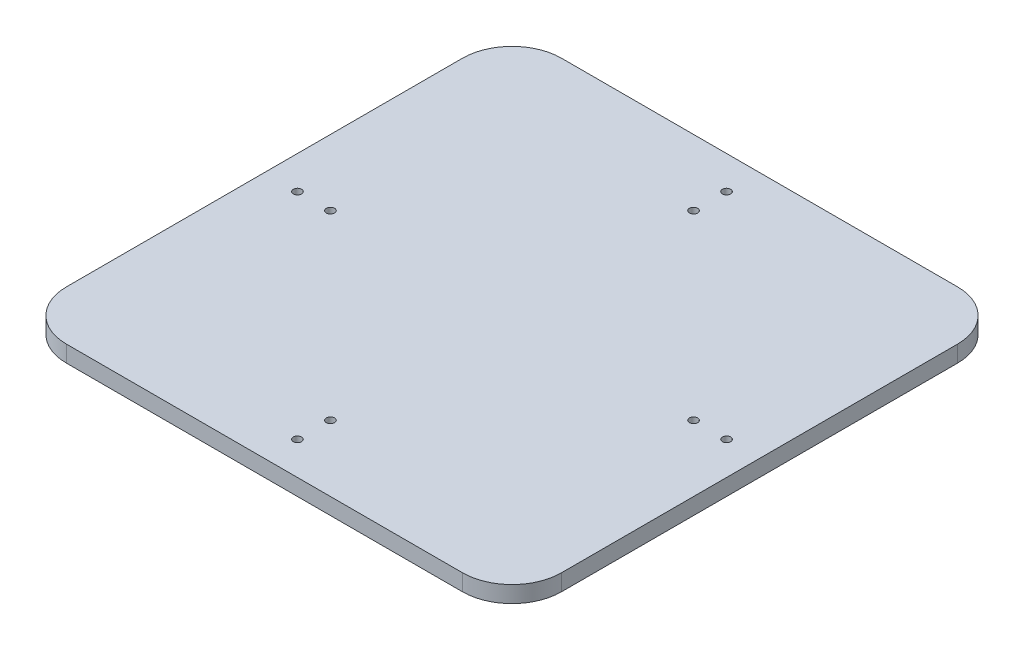
SolidWorks part; units mm, degrees
ref_plane "Front Plane" through (0, 0, 0) normal (0, 0, 1) x (1, 0, 0)
ref_plane "Top Plane" through (0, 0, 0) normal (0, 1, 0) x (1, 0, 0)
ref_plane "Right Plane" through (0, 0, 0) normal (1, 0, 0) x (0, 0, -1)
sketch "Sketch1" plane through (0, 0, 0) normal (0, 1, 0) x (1, 0, 0)
  line L0 (0, 75) -> (0, -75) construction
  line L1 (-75, -75) -> (75, -75)
  line L2 (-75, -75) -> (-75, 75)
  line L3 (-75, 75) -> (75, 75)
  line L4 (75, -75) -> (75, 75)
  line L5 (-75, -75) -> (75, 75) construction
  line L6 (-75, 75) -> (75, -75) construction
  line L7 (-75, 0) -> (75, 0) construction
  line L8 (-75, -60) -> (-60, -60) construction
  line L9 (-60, -60) -> (-60, -75) construction
  arc A2 (-75, -60) -> (-60, -75) centre (-60, -60) ccw
  arc A3 (75, -60) -> (60, -75) centre (60, -60) cw
  arc A4 (-75, 60) -> (-60, 75) centre (-60, 60) cw
  arc A5 (75, 60) -> (60, 75) centre (60, 60) ccw
  point P0 (0, 0)
  dimension "D6" = 15
  dimension "D4" = 15
  dimension "D1" = 150
  dimension "D2" = 150
extrude "Boss-Extrude3" add sketch "Sketch1" along normal blind 4 contours L4 A5 L3 A4 L2 A2 L1 A3
sketch "Sketch2" plane through (0, 4, 0) normal (0, 1, 0) x (1, 0, 0)
  line L0 (-60, 75) -> (60, 75)
  line L1 (75, 60) -> (75, -60)
  line L2 (60, -75) -> (-60, -75)
  line L3 (-75, -60) -> (-75, 60)
  line L4 (75, 0) -> (-75, 0) construction
  line L5 (0, 75) -> (0, -75) construction
  line L6 (0, 0) -> (-150, 0) construction
  line L7 (75, 0) -> (150, 0) construction
  line L8 (0, 75) -> (0, 150) construction
  line L9 (0, -75) -> (0, -150) construction
  line L10 (-150, 120) -> (-150, -120)
  line L11 (150, 120) -> (150, -120)
  line L12 (-120, 150) -> (120, 150)
  line L13 (-120, -150) -> (120, -150)
  line L14 (0, 76) -> (76, 76)
  line L15 (76, 76) -> (76, -76)
  line L16 (76, -76) -> (-76, -76)
  line L17 (-76, -76) -> (-76, 76)
  line L18 (-76, 76) -> (0, 76)
  arc A0 (-75, 60) -> (-60, 75) centre (-60, 60) cw
  arc A1 (60, 75) -> (75, 60) centre (60, 60) cw
  arc A2 (75, -60) -> (60, -75) centre (60, -60) cw
  arc A3 (-75, -60) -> (-60, -75) centre (-60, -60) ccw
  arc A4 (-120, -150) -> (-150, -120) centre (-120, -120) cw
  arc A5 (-150, 120) -> (-120, 150) centre (-120, 120) cw
  arc A6 (120, 150) -> (150, 120) centre (120, 120) cw
  arc A7 (150, -120) -> (120, -150) centre (120, -120) cw
  circle A8 centre (0, 130) radius 2.5
  circle A9 centre (0, 110) radius 2.5
  circle A10 centre (0, -110) radius 2.5
  circle A11 centre (0, -130) radius 2.5
  circle A12 centre (110, 0) radius 2.5
  circle A13 centre (130, 0) radius 2.5
  circle A14 centre (-130, 0) radius 2.5
  circle A15 centre (-110, 0) radius 2.5
  arc A16 (-60, 76) -> (-76, 60) centre (-60, 60) ccw
  arc A17 (60, 76) -> (76, 60) centre (60, 60) cw
  arc A18 (76, -60) -> (60, -76) centre (60, -60) cw
  arc A19 (-76, -60) -> (-60, -76) centre (-60, -60) ccw
  point P33 (-150, 0)
  point P36 (150, 0)
  point P39 (0, 150)
  point P42 (0, -150)
  dimension "D9" = 5
  dimension "D10" = 5
  dimension "D11" = 5
  dimension "D12" = 5
  dimension "D13" = 5
  dimension "D14" = 5
  dimension "D15" = 5
  dimension "D16" = 5
  dimension "D1" = 150
  dimension "D2" = 75
  dimension "D3" = 75
  dimension "D4" = 75
  dimension "D5" = 240
  dimension "D6" = 240
  dimension "D7" = 240
  dimension "D8" = 240
  dimension "D17" = 20
  dimension "D18" = 20
  dimension "D19" = 20
  dimension "D20" = 20
  dimension "D21" = 20
  dimension "D22" = 20
  dimension "D23" = 20
  dimension "D24" = 20
  dimension "D25" = 1
  dimension "D26" = 1
  dimension "D27" = 1
  dimension "D28" = 1
  dimension "D29" = 152
extrude "Boss-Extrude4" add sketch "Sketch2" along normal blind 10 separate body contours A19 L17 L16 | A7 L11 A6 L12 A5 L10 A4 L13 A15 A14 A13 A12 A11 A10 A9 A8 L17 L18 L14 L15 L16 | L15 A18 L16 | L14 A17 L15 | A16 L18 L17
sketch "Sketch3" plane through (0, 14, 0) normal (0, 1, 0) x (1, 0, 0)
  line L0 (-60, 76) -> (60, 76)
  line L1 (76, 60) -> (76, -60)
  line L2 (60, -76) -> (-60, -76)
  line L3 (-76, -60) -> (-76, 60)
  arc A0 (60, 76) -> (76, 60) centre (60, 60) cw
  arc A1 (76, -60) -> (60, -76) centre (60, -60) cw
  arc A2 (-60, -76) -> (-76, -60) centre (-60, -60) cw
  arc A3 (-76, 60) -> (-60, 76) centre (-60, 60) cw
extrude "Cut-Extrude1" cut sketch "Sketch3" against normal blind 52
sketch "Sketch4" plane through (0, 14, 0) normal (0, 1, 0) x (1, 0, 0)
  line L1 (-85.9344, 90.7531) -> (85.9344, 90.7531)
  line L2 (-85.9344, 90.7531) -> (-85.9344, -90.7531)
  line L3 (-85.9344, -90.7531) -> (85.9344, -90.7531)
  line L4 (85.9344, 90.7531) -> (85.9344, -90.7531)
  line L5 (-85.9344, 90.7531) -> (85.9344, -90.7531) construction
  line L6 (-85.9344, -90.7531) -> (85.9344, 90.7531) construction
  point P0 (0, 0)
extrude "Boss-Extrude5" add sketch "Sketch4" against normal blind 10
